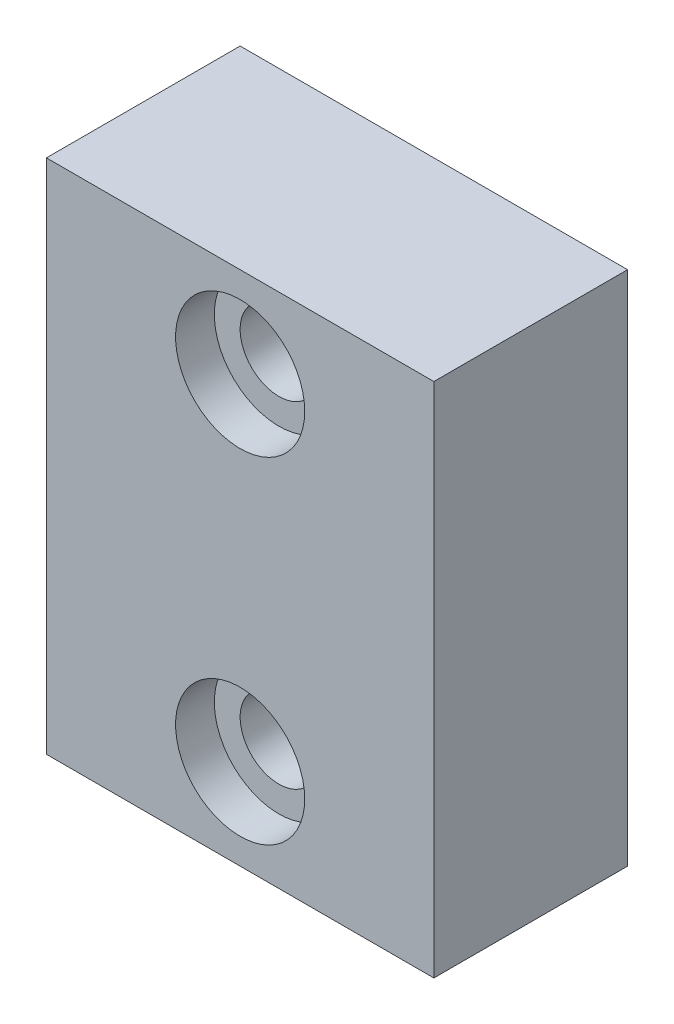
SolidWorks part; units mm, degrees
ref_plane "Ön Düzlem" through (0, 0, 0) normal (0, 0, 1) x (1, 0, 0)
ref_plane "Üst Düzlem" through (0, 0, 0) normal (0, 1, 0) x (1, 0, 0)
ref_plane "Sağ Düzlem" through (0, 0, 0) normal (1, 0, 0) x (0, 0, -1)
sketch "Çizim1" plane through (0, 0, 0) normal (0, 0, 1) x (1, 0, 0)
  line L1 (-6.5988, 3.2813) -> (8.4012, 3.2813)
  line L2 (-6.5988, 3.2813) -> (-6.5988, -16.7187)
  line L3 (-6.5988, -16.7187) -> (8.4012, -16.7187)
  line L4 (8.4012, 3.2813) -> (8.4012, -16.7187)
  dimension "D1" = 15
  dimension "D2" = 20
extrude "Yükseklik-Ekstrüzyon1" add sketch "Çizim1" along normal blind 7.5
sketch "Çizim2" plane through (0, 0, 7.5) normal (0, 0, 1) x (1, 0, 0)
  line L1 (-6.5988, 3.2813) -> (-6.5988, -16.7187) construction
  line L2 (8.4012, 3.2813) -> (-6.5988, 3.2813) construction
  line L3 (-6.5988, -16.7187) -> (8.4012, -16.7187) construction
  circle A1 centre (0.9012, -0.2187) radius 1.5
  circle A2 centre (0.9012, -13.2187) radius 1.5
  dimension "D1" = 3
  dimension "D2" = 7.5
  dimension "D4" = 3
  dimension "D3" = 3.5
  dimension "D5" = 3.5
  dimension "D6" = 7.5
extrude "Kes-Ekstrüzyon1" cut sketch "Çizim2" against normal blind 7.5 contours A1 | A2
sketch "Çizim3" plane through (0, 0, 7.5) normal (0, 0, 1) x (1, 0, 0)
  circle A0 centre (0.9012, -0.2187) radius 2.5
  circle A1 centre (0.9012, -13.2187) radius 2.5
  dimension "D1" = 5
  dimension "D2" = 5
extrude "Kes-Ekstrüzyon2" cut sketch "Çizim3" against normal blind 1.5
